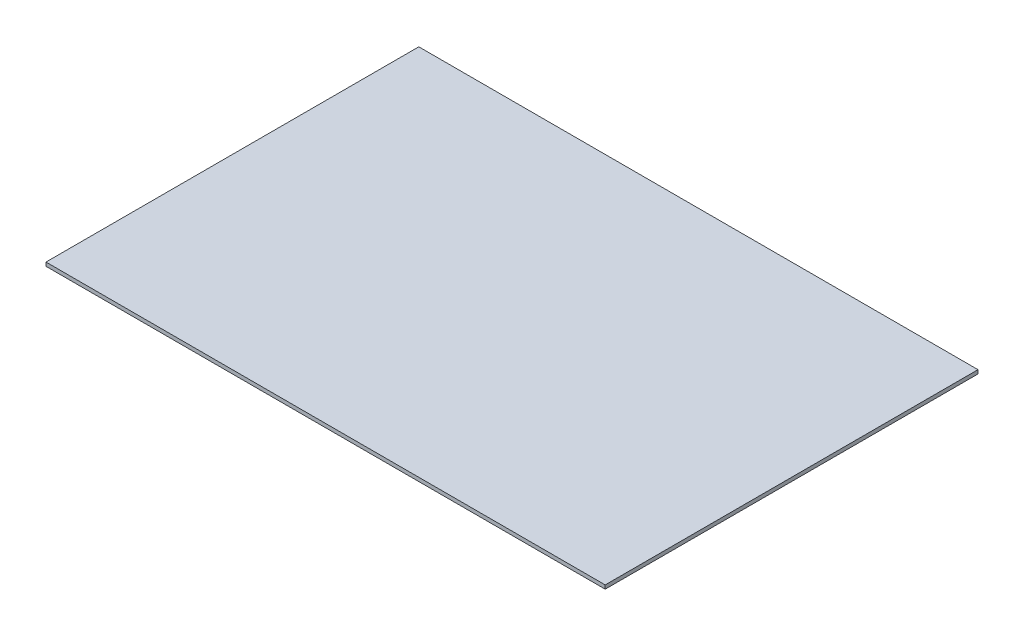
SolidWorks part; units mm, degrees
material "Thornel VCB-20 Carbon Cloth"
ref_plane "Front Plane" through (0, 0, 0) normal (0, 0, 1) x (1, 0, 0)
ref_plane "Top Plane" through (0, 0, 0) normal (0, 1, 0) x (1, 0, 0)
ref_plane "Right Plane" through (0, 0, 0) normal (1, 0, 0) x (0, 0, -1)
sketch "Sketch1" plane through (0, 0, 0) normal (0, 1, 0) x (1, 0, 0)
  line L0 (-150, 100) -> (-150, -100)
  line L1 (-150, -100) -> (150, -100)
  line L2 (150, -100) -> (150, 100)
  line L3 (150, 100) -> (-150, 100)
  point P4 (0, 100)
  point P6 (-150, 0)
  dimension "D1" = 300
  dimension "D2" = 200
extrude "Boss-Extrude1" add sketch "Sketch1" along normal blind 2
